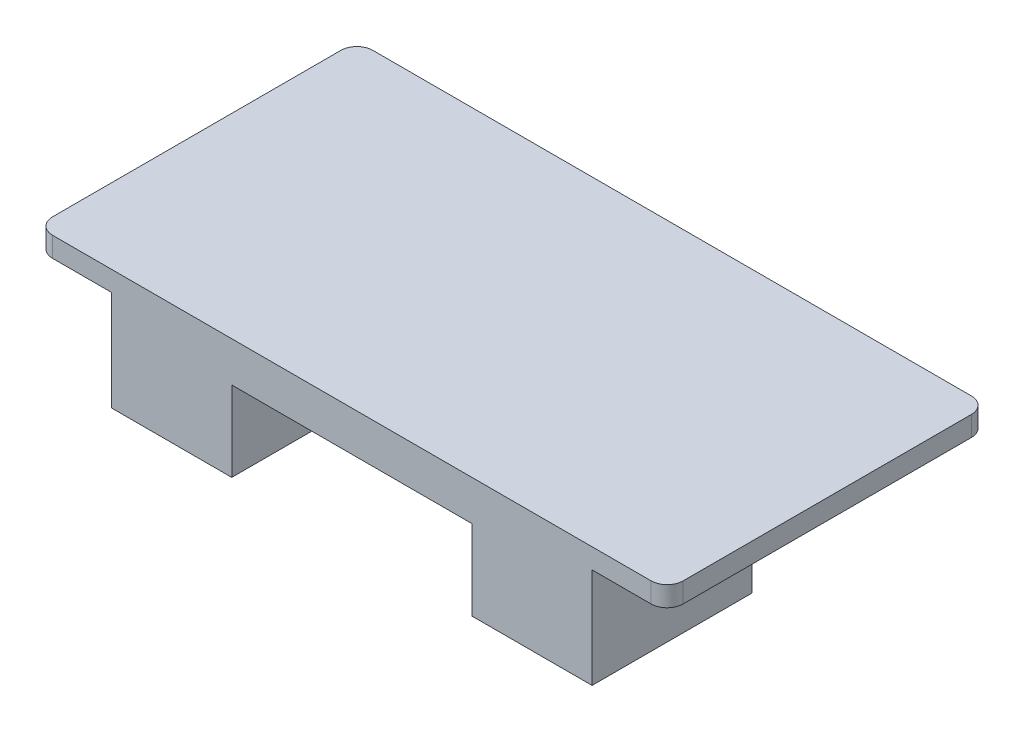
SolidWorks part; units mm, degrees
ref_plane "前视基准面" through (0, 0, 0) normal (0, 0, 1) x (1, 0, 0)
ref_plane "上视基准面" through (0, 0, 0) normal (0, 1, 0) x (1, 0, 0)
ref_plane "右视基准面" through (0, 0, 0) normal (1, 0, 0) x (0, 0, -1)
sketch "草图1" plane through (0, 0, 0) normal (0, 1, 0) x (1, 0, 0)
  line L1 (-60, 20) -> (60, 20)
  line L2 (-60, 20) -> (-60, -20)
  line L3 (-60, -20) -> (60, -20)
  line L4 (60, 20) -> (60, -20)
  dimension "D1" = 40
  dimension "D2" = 120
  dimension "D3" = 20
  dimension "D4" = 60
extrude "凸台-拉伸1" add sketch "草图1" along normal blind 25
sketch "草图2" plane through (0, 0, 0) normal (0, -1, 0) x (1, 0, 0)
  line L1 (-52.5, 11.75) -> (52.5, 11.75) construction
  line L2 (-52.5, 11.75) -> (-52.5, -11.75) construction
  line L3 (-52.5, -11.75) -> (52.5, -11.75) construction
  line L4 (52.5, 11.75) -> (52.5, -11.75) construction
  circle A0 centre (-52.5, 11.75) radius 2.75
  circle A1 centre (-52.5, -11.75) radius 2.75
  circle A2 centre (52.5, -11.75) radius 2.75
  circle A3 centre (52.5, 11.75) radius 2.75
  dimension "D5" = 5.5
  dimension "D1" = 23.5
  dimension "D2" = 105
  dimension "D3" = 52.5
  dimension "D4" = 11.75
extrude "切除-拉伸1" cut sketch "草图2" against normal blind 25
sketch "草图5" plane through (0, 25, 0) normal (0, 1, 0) x (1, 0, 0)
  line L1 (-78.75, 60) -> (78.75, 60)
  line L2 (-78.75, 60) -> (-78.75, -20)
  line L3 (-78.75, -20) -> (78.75, -20)
  line L4 (78.75, 60) -> (78.75, -20)
  dimension "D1" = 157.5
  dimension "D2" = 80
  dimension "D3" = 78.75
  dimension "D4" = 20
extrude "凸台-拉伸2" add sketch "草图5" along normal blind 5
sketch "草图6" plane through (0, 0, 0) normal (0, -1, 0) x (1, 0, 0)
  line L0 (-60, 20) -> (60, 20) construction
  line L1 (-30, 20) -> (30, 20)
  line L2 (-30, 20) -> (-30, -20)
  line L3 (-30, -20) -> (30, -20)
  line L4 (30, 20) -> (30, -20)
  line L5 (60, -20) -> (-60, -20) construction
  dimension "D1" = 60
  dimension "D2" = 30
extrude "切除-拉伸3" cut sketch "草图6" against normal blind 20
fillet "圆角1" radius 4 4 edges at (-78.75, 27.5, 20) (-78.75, 27.5, -60) (78.75, 27.5, 20) (78.75, 27.5, -60)
chamfer "倒角1" distance 0.5 angle 45 4 edges at (52.5, 0, 9) (52.5, 0, -14.5) (-52.5, 0, 9) (-52.5, 0, -14.5)
